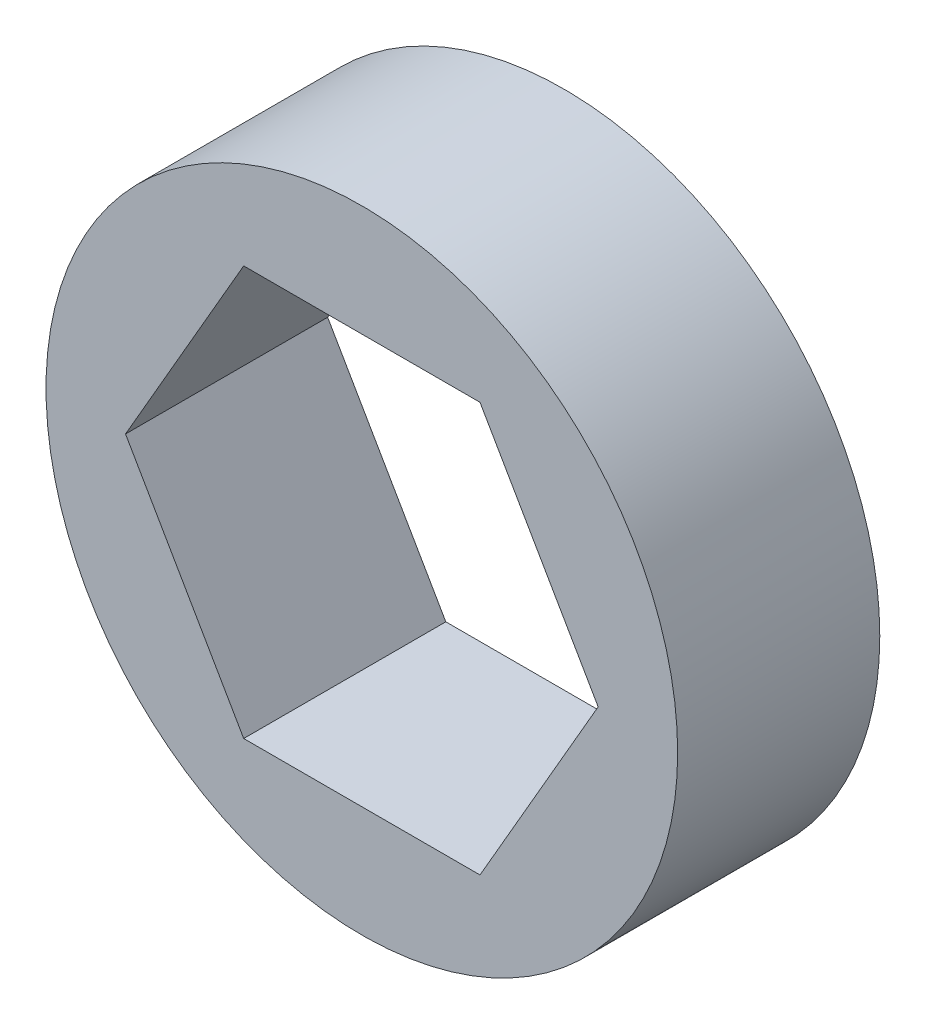
SolidWorks part; units mm, degrees
material "ABS"
ref_plane "Front" through (0, 0, 0) normal (0, 0, 1) x (1, 0, 0)
ref_plane "Top" through (0, 0, 0) normal (0, 1, 0) x (1, 0, 0)
ref_plane "Right" through (0, 0, 0) normal (1, 0, 0) x (0, 0, -1)
sketch "Sketch1" plane through (0, 0, 0) normal (0, 0, 1) x (1, 0, 0)
  line L1 (2.9696, -5.1435) -> (5.9392, 0)
  line L2 (5.9392, 0) -> (2.9696, 5.1435)
  line L3 (2.9696, 5.1435) -> (-2.9696, 5.1435)
  line L4 (-2.9696, 5.1435) -> (-5.9392, 0)
  line L5 (-5.9392, 0) -> (-2.9696, -5.1435)
  line L6 (-2.9696, -5.1435) -> (2.9696, -5.1435)
  circle A0 centre (0, 0) radius 7.9375
  circle A1 centre (0, 0) radius 5.1435 construction
  dimension "D1" = 15.875
  dimension "D2" = 10.287
extrude "Boss-Extrude1" add sketch "Sketch1" along normal blind 5.08
